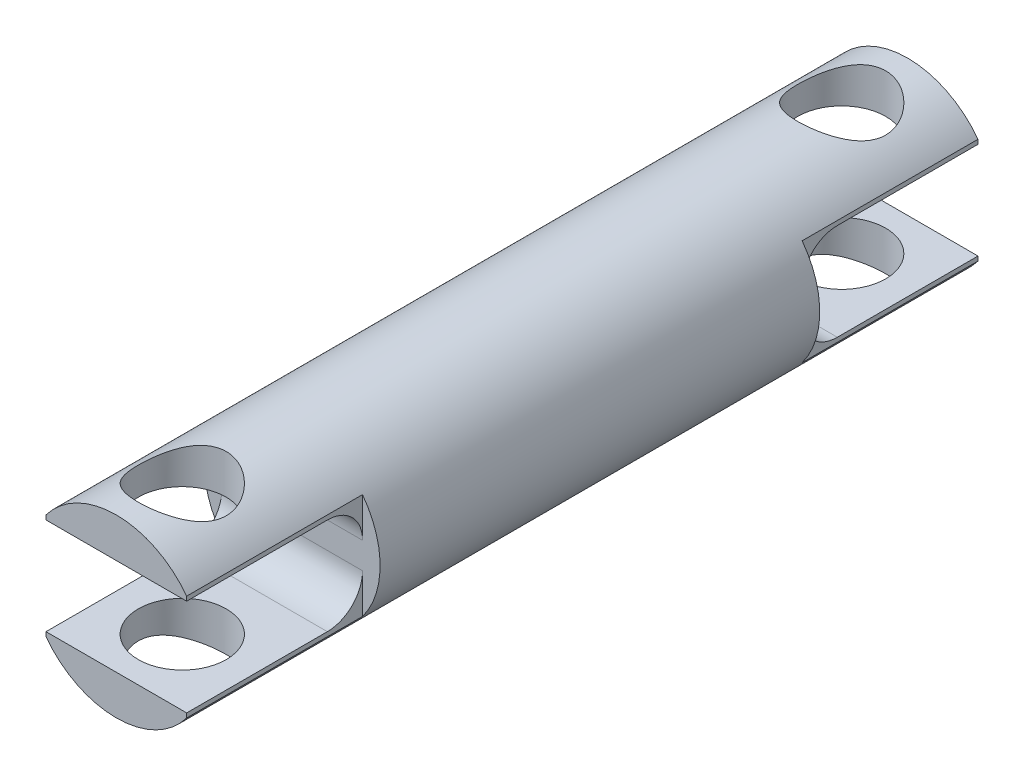
SolidWorks part; units mm, degrees
ref_plane "Płaszczyzna przednia" through (0, 0, 0) normal (0, 0, 1) x (1, 0, 0)
ref_plane "Płaszczyzna górna" through (0, 0, 0) normal (0, 1, 0) x (1, 0, 0)
ref_plane "Płaszczyzna prawa" through (0, 0, 0) normal (1, 0, 0) x (0, 0, -1)
sketch "Szkic1" plane through (0, 0, 0) normal (0, 0, 1) x (1, 0, 0)
  circle A0 centre (0, 0) radius 20
  dimension "D1" = 40
extrude "Dodanie-wyciągnięcie1" add sketch "Szkic1" along normal blind 50 contours A0
sketch "Szkic6" plane through (0, 0, 50) normal (0, 0, 1) x (1, 0, 0)
  line L0 (-16, 12) -> (-16, 11)
  line L1 (-16, 11) -> (16, 11)
  line L2 (16, 11) -> (16, 12)
  line L3 (0, 0) -> (13.4968, 0) construction
  line L4 (16, -11) -> (16, -12)
  line L5 (-16, -11) -> (16, -11)
  line L6 (-16, -12) -> (-16, -11)
  circle A0 centre (0, 0) radius 20 construction
  arc A1 (-16, -12) -> (16, -12) centre (0, 0) ccw
  arc A2 (16, 12) -> (-16, 12) centre (0, 0) ccw
  dimension "D1" = 11
  dimension "D2" = 16
  dimension "D3" = 16
extrude "Dodanie-wyciągnięcie4" add sketch "Szkic6" along normal blind 40
sketch "Szkic7" plane through (0, -11, 0) normal (0, 1, 0) x (1, 0, 0)
  line L0 (16, -90) -> (-16, -90) construction
  line L1 (16, -50) -> (-16, -50) construction
  circle A0 centre (0, -75) radius 10
  point P4 (-5.5425, -115)
  point P7 (0, -50)
  dimension "D1" = 20
  dimension "D2" = 15
extrude "Wytnij-wyciągnięcie1" cut sketch "Szkic7" along normal blind 40 and the other way up to next
fillet "Zaokrąglenie1" radius 8 2 edges at (0, -11, 50) (0, 11, 50)
mirror "Lustro2" about plane through (0, 0, 0) normal (0, 0, 1) of "Dodanie-wyciągnięcie1", "Zaokrąglenie1", "Wytnij-wyciągnięcie1", "Dodanie-wyciągnięcie4"
